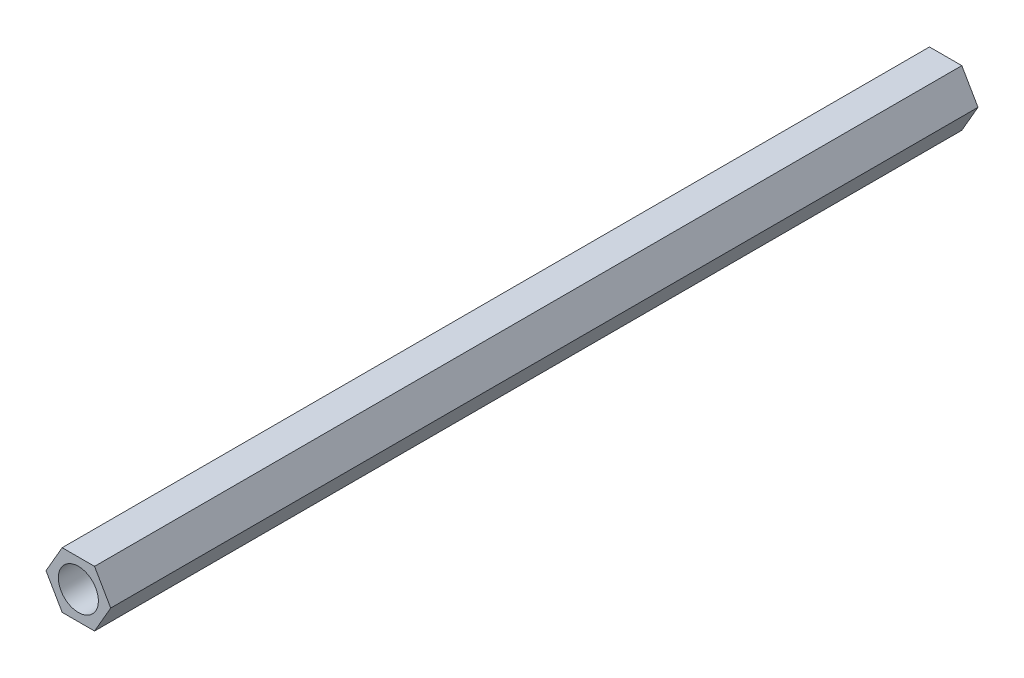
SolidWorks part; units mm, degrees
ref_plane "前视基准面" through (0, 0, 0) normal (0, 0, 1) x (1, 0, 0)
ref_plane "上视基准面" through (0, 0, 0) normal (0, 1, 0) x (1, 0, 0)
ref_plane "右视基准面" through (0, 0, 0) normal (1, 0, 0) x (0, 0, -1)
other "Configuration Table"
sketch "草图1" plane through (0, 0, 0) normal (0, 0, 1) x (1, 0, 0)
  line L1 (2.4249, 0) -> (1.2124, 2.1)
  line L2 (1.2124, 2.1) -> (-1.2124, 2.1)
  line L3 (-1.2124, 2.1) -> (-2.4249, 0)
  line L4 (-2.4249, 0) -> (-1.2124, -2.1)
  line L5 (-1.2124, -2.1) -> (1.2124, -2.1)
  line L6 (1.2124, -2.1) -> (2.4249, 0)
  circle A0 centre (0, 0) radius 2.1 construction
  circle A1 centre (0, 0) radius 1.5
  dimension "D1" = 4.2
extrude "凸台-拉伸1" add sketch "草图1" along normal blind 65
